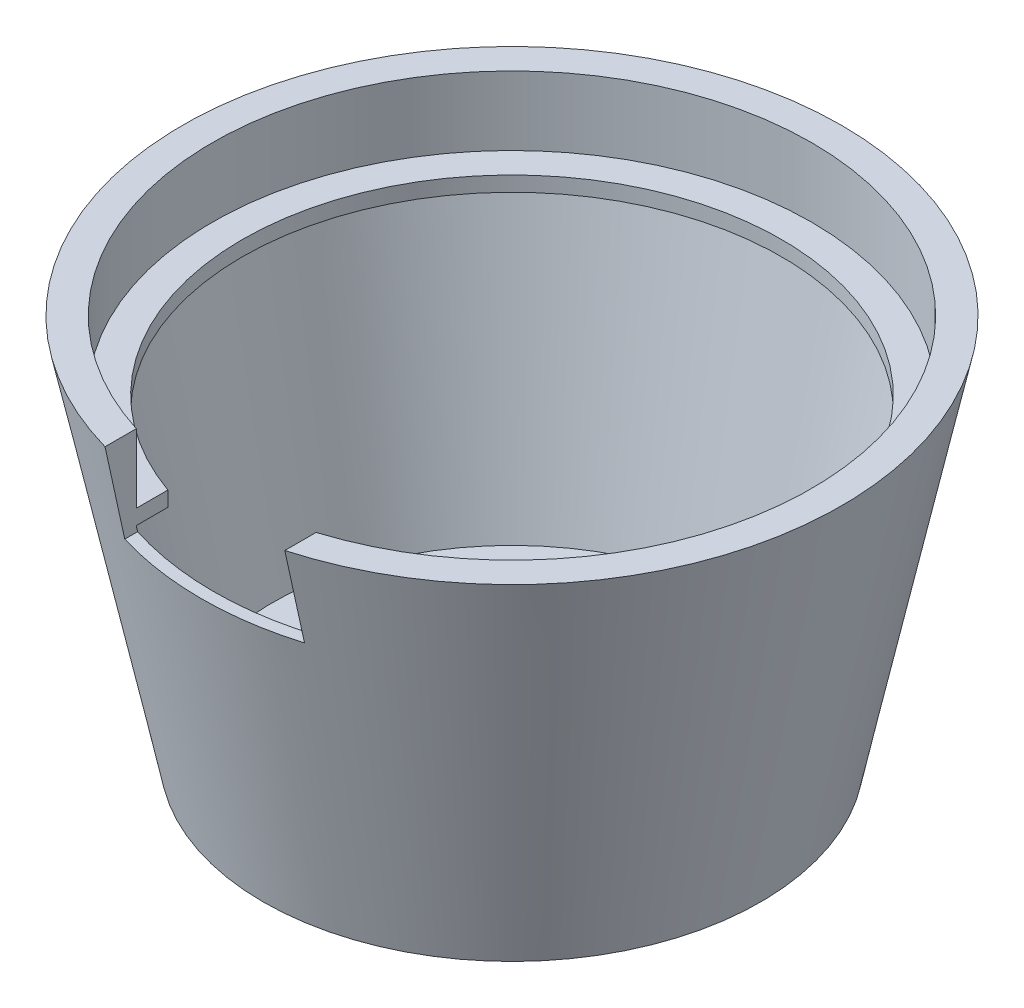
SolidWorks part; units mm, degrees
ref_plane "前基準面" through (0, 0, 0) normal (0, 0, 1) x (1, 0, 0)
ref_plane "上基準面" through (0, 0, 0) normal (0, 1, 0) x (1, 0, 0)
ref_plane "右基準面" through (0, 0, 0) normal (1, 0, 0) x (0, 0, -1)
sketch "草圖1" plane through (0, 0, 0) normal (1, 0, 0) x (0, 0, -1)
  line L0 (0, 0) -> (83.0345, 0)
  line L1 (83.0345, 0) -> (110, 128)
  line L2 (110, 128) -> (100, 128)
  line L3 (100, 128) -> (100, 105)
  line L4 (100, 105) -> (90, 105)
  line L5 (90, 105) -> (90, 100)
  line L6 (90, 100) -> (100.0135, 100)
  line L7 (100.0135, 100) -> (80, 5)
  line L8 (80, 5) -> (0, 5)
  line L9 (0, 5) -> (0, 0)
  dimension "D1" = 100
  dimension "D2" = 23
  dimension "D3" = 4
  dimension "D4" = 110
  dimension "D5" = 100
  dimension "D6" = 5
  dimension "D7" = 10
  dimension "D8" = 5
  dimension "D9" = 80
revolve "旋轉1" add sketch "草圖1" angle 360 about L9
sketch "草圖2" plane through (0, 128, 0) normal (0, 1, 0) x (1, 0, 0)
  line L0 (0, 0) -> (0, -69.8146) construction
  line L1 (-30, -69.8146) -> (30, -69.8146)
  line L2 (-30, -69.8146) -> (-30, -127.4278)
  line L3 (-30, -127.4278) -> (30, -127.4278)
  line L4 (30, -69.8146) -> (30, -127.4278)
  dimension "D1" = 60
extrude "除料-伸長1" cut sketch "草圖2" against normal blind 30
